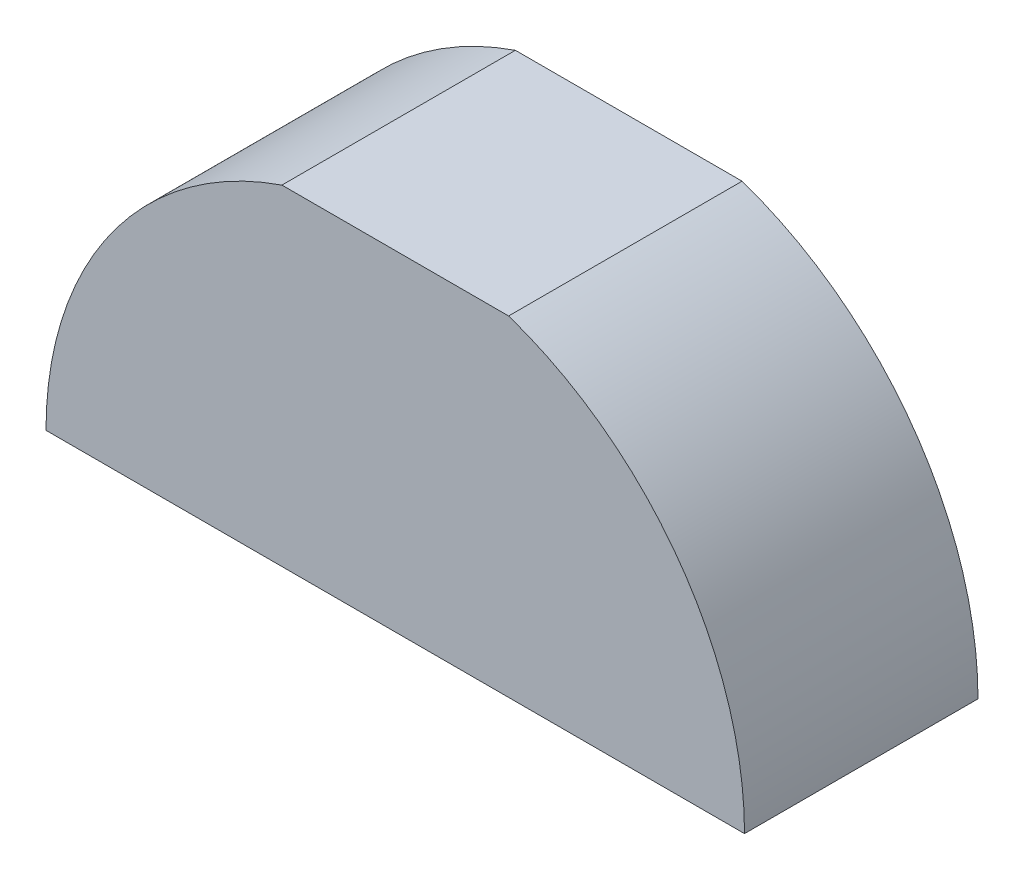
SolidWorks part; units mm, degrees
ref_plane "Front Plane" through (0, 0, 0) normal (0, 0, 1) x (1, 0, 0)
ref_plane "Top Plane" through (0, 0, 0) normal (0, 1, 0) x (1, 0, 0)
ref_plane "Right Plane" through (0, 0, 0) normal (1, 0, 0) x (0, 0, -1)
sketch "Sketch2" plane through (0, 0, 0) normal (0, 0, 1) x (1, 0, 0)
  line L0 (-9.7051, 0) -> (-0.2055, 0)
  arc A0 (-9.7051, 0) -> (-0.2055, 0) centre (-4.9553, 0) cw
  dimension "D1" = 9.4996
extrude "Boss-Extrude2" add sketch "Sketch2" along normal blind 3.175
sketch "Sketch5" plane through (0, 0, 0) normal (0, 0, 1) x (1, 0, 0)
  line L0 (-6.4968, 4.4927) -> (-3.4138, 4.4927)
  arc A0 (-0.2055, 0) -> (-9.7051, 0) centre (-4.9553, 0) ccw construction
extrude "Cut-Extrude2" cut sketch "Sketch5" against normal through all and the other way through all
